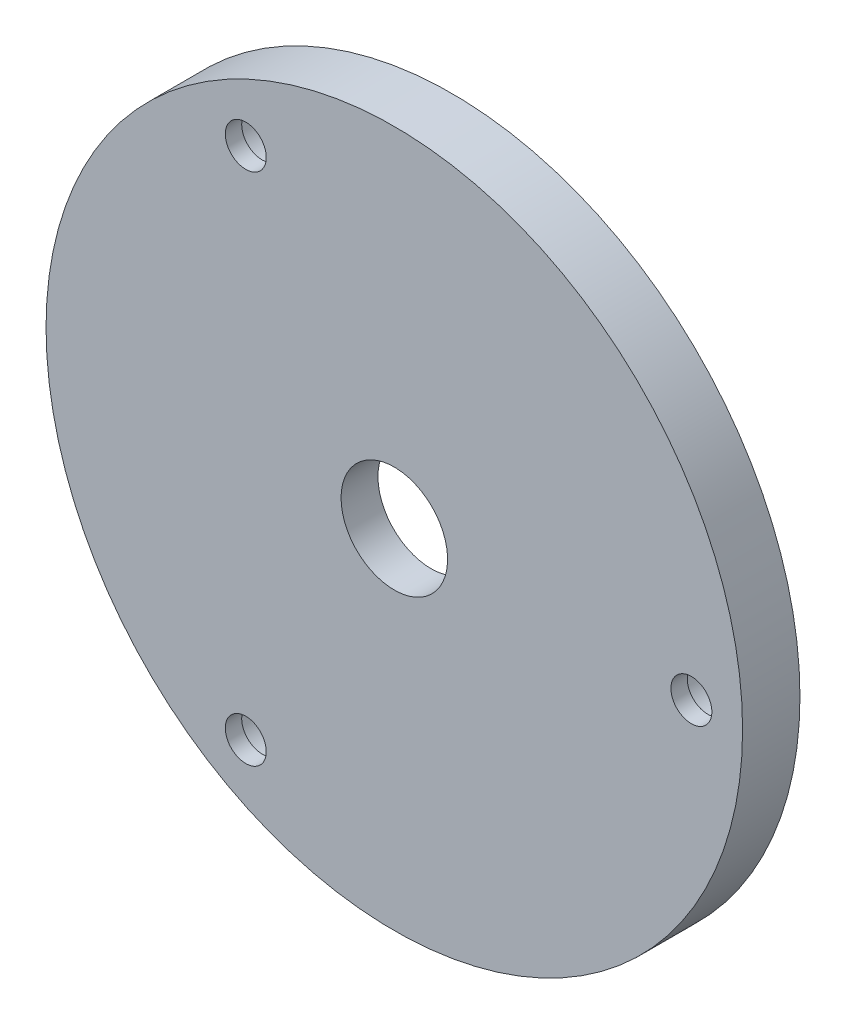
SolidWorks part; units mm, degrees
ref_plane "前视基准面" through (0, 0, 0) normal (0, 0, 1) x (1, 0, 0)
ref_plane "上视基准面" through (0, 0, 0) normal (0, 1, 0) x (1, 0, 0)
ref_plane "右视基准面" through (0, 0, 0) normal (1, 0, 0) x (0, 0, -1)
sketch "草图1" plane through (0, 0, 0) normal (0, 1, 0) x (1, 0, 0)
  line L0 (85, 0) -> (0, 0)
  line L1 (0, 0) -> (0, -14)
  line L2 (0, -14) -> (85, -14)
  line L3 (85, -14) -> (85, 0)
  line L4 (0, 0) -> (0, -14) construction
revolve "旋转1" add sketch "草图1" angle 360 about L4
hole_wizard "M24 六角头螺栓的柱形沉头孔1" positions "草图3" profile "草图2" counterbore size "M24" standard "ANSI Metric"
sketch "草图3" plane through (0, 0, 0) normal (0, 0, -1) x (-1, 0, 0)
  point P0 (0, 0)
sketch "草图2" plane through (0, 0, 0) normal (1, 0, 0) x (0, 1, 0)
  line L0 (0, 0) -> (0, 14)
  line L1 (0, 14) -> (13, 14)
  line L3 (13, 14) -> (13, 5)
  line L4 (13, 5) -> (60, 5)
  line L5 (60, 5) -> (60, 0)
  line L7 (60, 0) -> (0, 0)
  line L11 (0, -6.35) -> (0, 107.95) construction
  dimension "通孔孔直径" = 26
  dimension "通孔孔深度" = 14
  dimension "柱形沉头孔直径" = 120
  dimension "柱形沉头孔深度" = 5
hole_wizard "M8 六角头螺栓的柱形沉头孔1" positions "草图5" profile "草图4" counterbore size "M8" standard "ANSI Metric" end condition through all
sketch "草图5" plane through (0, 0, 0) normal (0, 0, -1) x (-1, 0, 0)
  point P0 (36.25, 62.7868)
  point P1 (-72.5, 0)
  point P2 (36.25, -62.7868)
  dimension "D1" = 72.5
  dimension "D2" = 72.5
  dimension "D3" = 72.5
  dimension "D4" = 120
  dimension "D5" = 120
sketch "草图4" plane through (-36.25, 62.7868, 0) normal (1, 0, 0) x (0, 1, 0)
  line L0 (0, 0) -> (0, 14)
  line L1 (0, 14) -> (5, 14)
  line L3 (5, 14) -> (5, 10)
  line L4 (5, 10) -> (8, 10)
  line L5 (8, 10) -> (8, 0)
  line L7 (8, 0) -> (0, 0)
  line L11 (0, -6.35) -> (0, 107.95) construction
  dimension "通孔孔直径" = 10
  dimension "通孔孔深度" = 14
  dimension "柱形沉头孔直径" = 16
  dimension "柱形沉头孔深度" = 10
